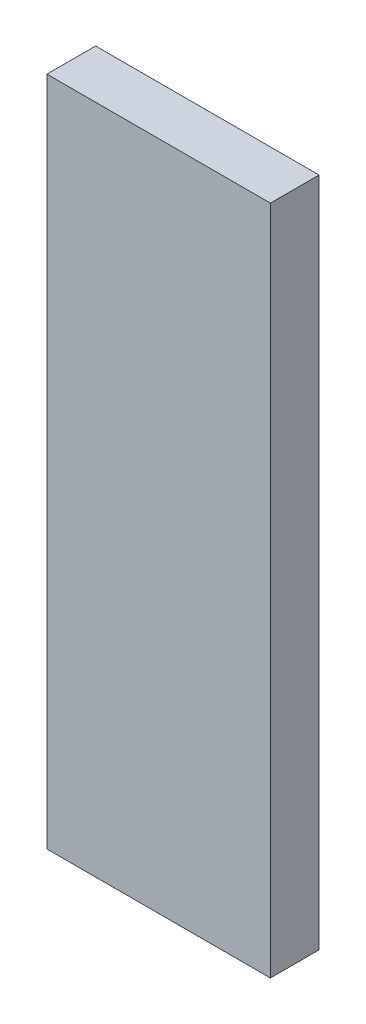
SolidWorks part; units mm, degrees
ref_plane "Front Plane" through (0, 0, 0) normal (0, 0, 1) x (1, 0, 0)
ref_plane "Top Plane" through (0, 0, 0) normal (0, 1, 0) x (1, 0, 0)
ref_plane "Right Plane" through (0, 0, 0) normal (1, 0, 0) x (0, 0, -1)
sketch "Sketch1" plane through (0, 0, 0) normal (0, 0, 1) x (1, 0, 0)
  line L1 (-21.7182, 31.0897) -> (10.4018, 31.0897)
  line L2 (-21.7182, 31.0897) -> (-21.7182, -65.3703)
  line L3 (-21.7182, -65.3703) -> (10.4018, -65.3703)
  line L4 (10.4018, 31.0897) -> (10.4018, -65.3703)
  dimension "D1" = 32.12
  dimension "D2" = 96.46
extrude "Boss-Extrude1" add sketch "Sketch1" along normal blind 7
